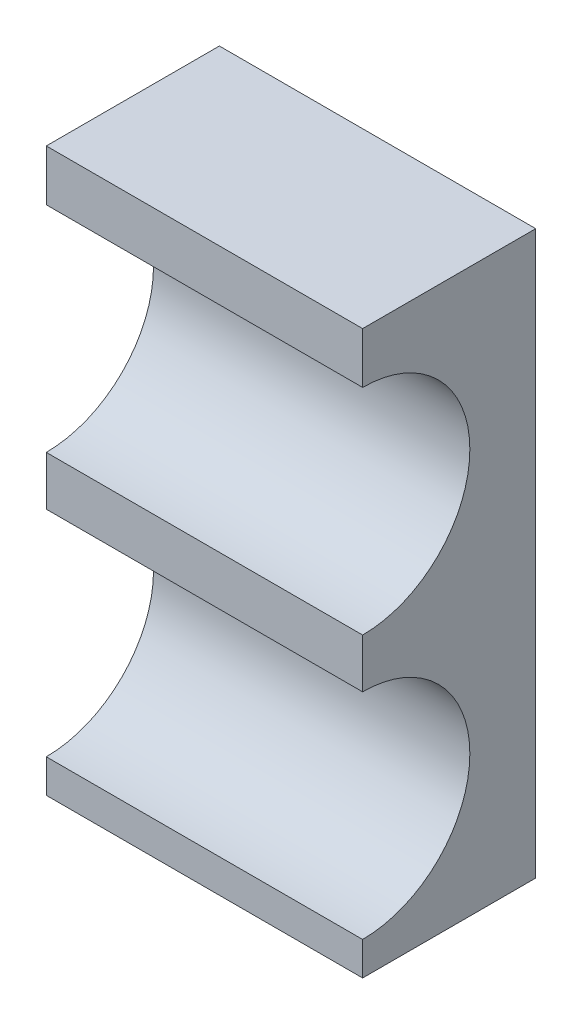
SolidWorks part; units mm, degrees
ref_plane "Front Plane" through (0, 0, 0) normal (0, 0, 1) x (1, 0, 0)
ref_plane "Top Plane" through (0, 0, 0) normal (0, 1, 0) x (1, 0, 0)
ref_plane "Right Plane" through (0, 0, 0) normal (1, 0, 0) x (0, 0, -1)
sketch "Sketch1" plane through (0, 0, 0) normal (1, 0, 0) x (0, 0, -1)
  line L1 (4.924, -8) -> (-4.924, -8)
  line L2 (4.924, -8) -> (4.924, 8)
  line L3 (4.924, 8) -> (-4.924, 8)
  line L4 (-4.924, -8) -> (-4.924, 8)
  line L5 (4.924, -8) -> (-4.924, 8) construction
  line L6 (4.924, 8) -> (-4.924, -8) construction
  circle A0 centre (0, -3.5) radius 3
  circle A1 centre (0, 3.5) radius 3
  point P0 (0, 0)
  dimension "D2" = 6
  dimension "D3" = 6
  dimension "D1" = 16
  dimension "D4" = 3.5
  dimension "D5" = 3.5
extrude "Boss-Extrude1" add sketch "Sketch1" along normal blind 9 contours L2 L3 L4 L1
sketch "Sketch3" plane through (0, 0, 0) normal (-1, 0, 0) x (0, 0, 1)
  line L2 (-4.924, -8) -> (4.924, -8) construction
  circle A0 centre (0, 3.5) radius 3.05
  circle A1 centre (0, -4) radius 3.05
  dimension "D1" = 6.1
  dimension "D2" = 6.1
  dimension "D3" = 7.5
  dimension "D4" = 4
extrude "Cut-Extrude1" cut sketch "Sketch3" against normal blind 9
sketch "Sketch4" plane through (0, 0, 0) normal (-1, 0, 0) x (0, 0, 1)
  line L1 (0, 10.077) -> (8.1108, 10.077)
  line L2 (0, 10.077) -> (0, -10.077)
  line L3 (0, -10.077) -> (8.1108, -10.077)
  line L4 (8.1108, 10.077) -> (8.1108, -10.077)
  point P4 (0, 0)
extrude "Cut-Extrude2" cut sketch "Sketch4" against normal blind 9
